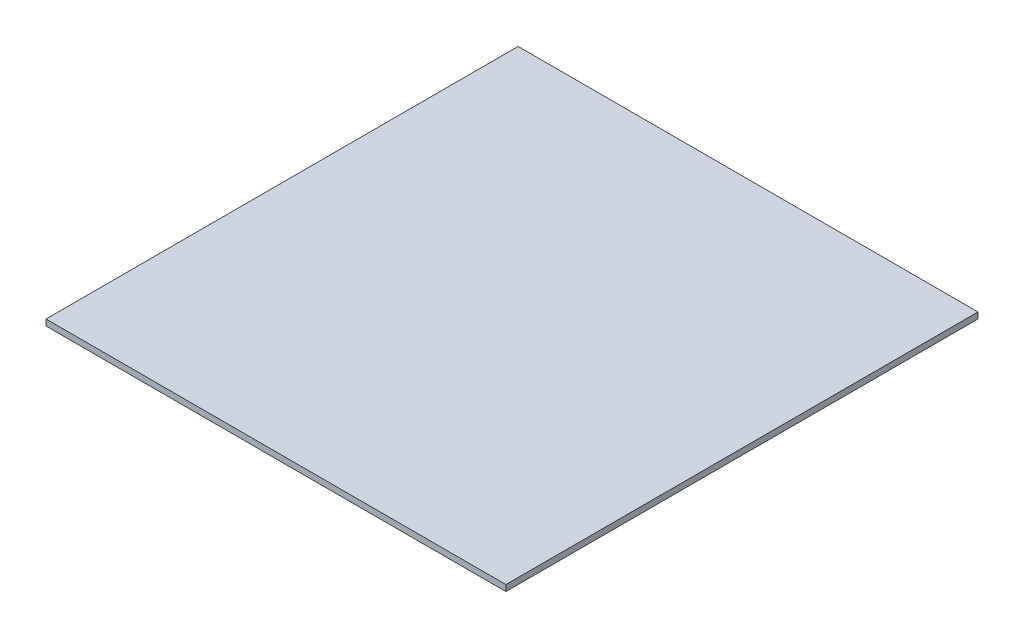
SolidWorks part; units mm, degrees
ref_plane "Front Plane" through (0, 0, 0) normal (0, 0, 1) x (1, 0, 0)
ref_plane "Top Plane" through (0, 0, 0) normal (0, 1, 0) x (1, 0, 0)
ref_plane "Right Plane" through (0, 0, 0) normal (1, 0, 0) x (0, 0, -1)
sketch "Sketch1" plane through (0, 0, 0) normal (0, 1, 0) x (1, 0, 0)
  line L5 (-75.35, 77.35) -> (75.35, 77.35)
  line L6 (-75.35, 77.35) -> (-75.35, -77.35)
  line L7 (-75.35, -77.35) -> (75.35, -77.35)
  line L8 (75.35, 77.35) -> (75.35, -77.35)
  line L9 (-75.35, 77.35) -> (75.35, -77.35) construction
  line L10 (-75.35, -77.35) -> (75.35, 77.35) construction
  point P0 (0, 0)
  dimension "D1" = 150.7
  dimension "D2" = 154.7
extrude "Boss-Extrude1" add sketch "Sketch1" along normal blind 2
